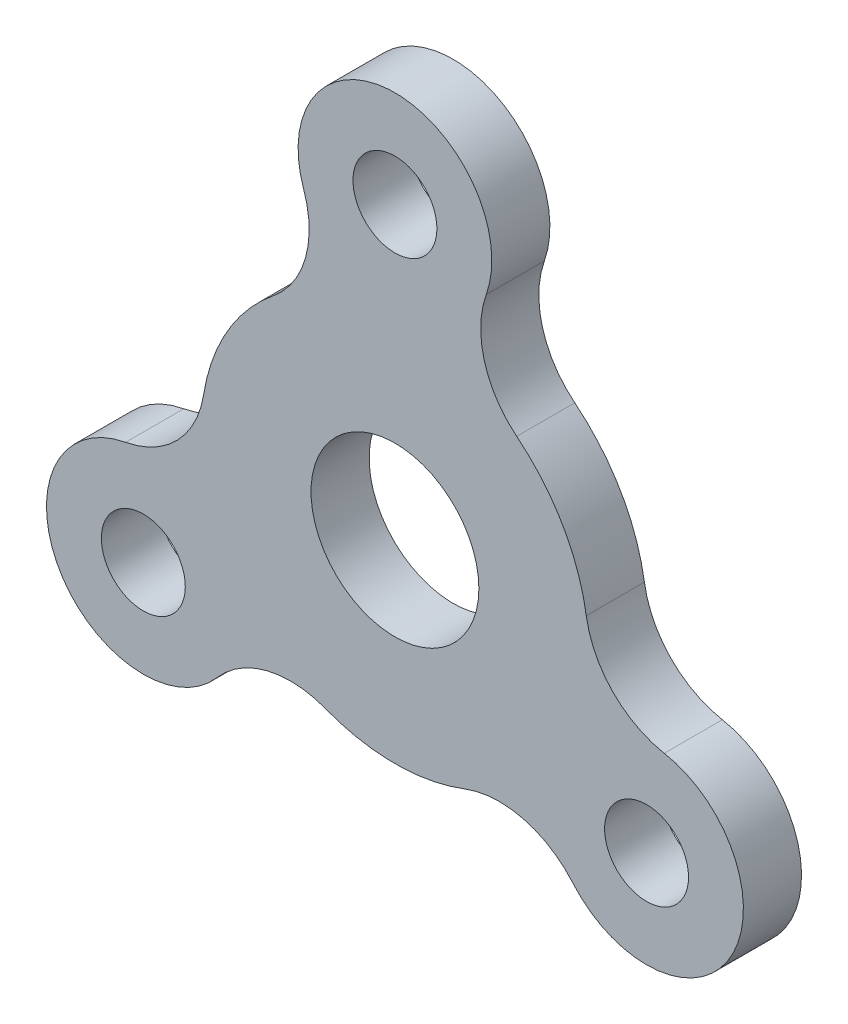
SolidWorks part; units mm, degrees
material "Alloy Steel"
ref_plane "Front Plane" through (0, 0, 0) normal (0, 0, 1) x (1, 0, 0)
ref_plane "Top Plane" through (0, 0, 0) normal (0, 1, 0) x (1, 0, 0)
ref_plane "Right Plane" through (0, 0, 0) normal (1, 0, 0) x (0, 0, -1)
sketch "Sketch1" plane through (0, 0, 0) normal (0, 0, 1) x (1, 0, 0)
  line L0 (0, 0) -> (-389.7114, -225) construction
  line L1 (-389.7114, -225) -> (389.7114, -225) construction
  line L2 (389.7114, -225) -> (0, 0) construction
  line L3 (0, 0) -> (0, 450) construction
  circle A0 centre (0, 0) radius 600 construction
  arc A1 (-188.5618, 233.3333) -> (-296.3535, 46.6326) centre (0, 0) ccw
  arc A2 (-417.1208, -77.5255) -> (-275.6995, -322.4745) centre (-389.7114, -225) ccw
  arc A3 (275.6995, -322.4745) -> (417.1208, -77.5255) centre (389.7114, -225) ccw
  arc A4 (141.4214, 400) -> (-141.4214, 400) centre (0, 450) ccw
  arc A5 (-107.7917, -279.966) -> (-275.6995, -322.4745) centre (-161.6875, -419.949) ccw
  arc A6 (-188.5618, 233.3333) -> (-141.4214, 400) centre (-282.8427, 350) ccw
  arc A7 (275.6995, -322.4745) -> (107.7917, -279.966) centre (161.6875, -419.949) ccw
  arc A8 (141.4214, 400) -> (188.5618, 233.3333) centre (282.8427, 350) ccw
  arc A9 (-417.1208, -77.5255) -> (-296.3535, 46.6326) centre (-444.5302, 69.949) ccw
  arc A10 (296.3535, 46.6326) -> (417.1208, -77.5255) centre (444.5302, 69.949) ccw
  arc A11 (296.3535, 46.6326) -> (188.5618, 233.3333) centre (0, 0) ccw
  arc A12 (-107.7917, -279.966) -> (107.7917, -279.966) centre (0, 0) ccw
  dimension "D1" = 1200
  dimension "D2" = 600
  dimension "D3" = 120
  dimension "D4" = 120
extrude "Boss-Extrude1" add sketch "Sketch1" along normal blind 90
sketch "Sketch2" plane through (0, 0, 90) normal (0, 0, 1) x (1, 0, 0)
  circle A0 centre (0, 450) radius 65
  circle A1 centre (-389.7114, -225) radius 65
  circle A2 centre (389.7114, -225) radius 65
  dimension "D1" = 130
extrude "Cut-Extrude1" cut sketch "Sketch2" against normal through all
sketch "Sketch3" plane through (0, 0, 90) normal (0, 0, 1) x (1, 0, 0)
  circle A0 centre (0, 0) radius 130
  dimension "D1" = 260
extrude "Cut-Extrude2" cut sketch "Sketch3" against normal through all
